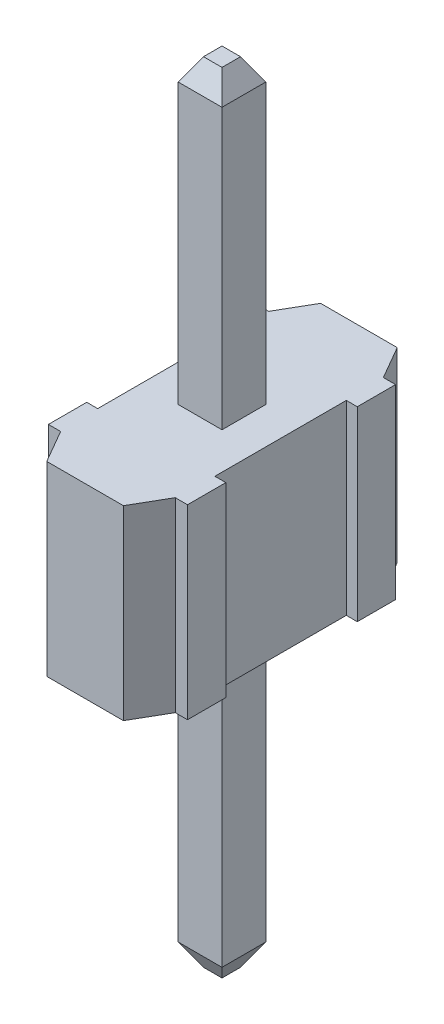
SolidWorks part; units mm, degrees
ref_plane "前视基准面" through (0, 0, 0) normal (0, 0, 1) x (1, 0, 0)
ref_plane "上视基准面" through (0, 0, 0) normal (0, 1, 0) x (1, 0, 0)
ref_plane "右视基准面" through (0, 0, 0) normal (1, 0, 0) x (0, 0, -1)
sketch "草图1" plane through (0, 0, 0) normal (0, 1, 0) x (1, 0, 0)
  line L0 (-1.2877, 0) -> (3.6912, 0) construction
  line L1 (-0.635, -1.25) -> (0.635, -1.25) construction
  line L2 (-0.635, -1.25) -> (-0.635, 1.25) construction
  line L3 (-0.635, 1.25) -> (0.635, 1.25) construction
  line L4 (0.635, -1.25) -> (0.635, 1.25) construction
  line L5 (-0.635, -1.25) -> (0.635, 1.25) construction
  line L6 (-0.635, 1.25) -> (0.635, -1.25) construction
  line L7 (0, 0) -> (-0.635, 0) construction
  line L8 (0, 0) -> (0, -1.25) construction
  line L9 (-0.635, -0.95) -> (-0.5232, -0.95)
  line L10 (-0.5232, -0.95) -> (-0.35, -1.25)
  line L11 (-0.35, -1.25) -> (0.35, -1.25)
  line L12 (-0.635, -0.95) -> (-0.635, -0.6)
  line L13 (-0.635, -0.6) -> (-0.535, -0.6)
  line L14 (-0.535, -0.6) -> (-0.535, 0.6)
  line L15 (-0.35, 1.25) -> (0.35, 1.25)
  line L17 (-0.635, 0.95) -> (-0.5232, 0.95)
  line L18 (-0.635, 0.95) -> (-0.635, 0.6)
  line L19 (-0.635, 0.6) -> (-0.535, 0.6)
  line L20 (-0.5232, 0.95) -> (-0.35, 1.25)
  line L21 (0.5232, 0.95) -> (0.35, 1.25)
  line L22 (0.5232, -0.95) -> (0.35, -1.25)
  line L23 (0.635, -0.95) -> (0.5232, -0.95)
  line L24 (0.635, -0.95) -> (0.635, -0.6)
  line L25 (0.635, -0.6) -> (0.535, -0.6)
  line L26 (0.535, -0.6) -> (0.535, 0.6)
  line L27 (0.635, 0.6) -> (0.535, 0.6)
  line L28 (0.635, 0.95) -> (0.635, 0.6)
  line L29 (0.635, 0.95) -> (0.5232, 0.95)
  point P0 (0, 0)
  point P23 (-0.535, 0)
  point P24 (0, 1.25)
  dimension "D1" = 120
  dimension "D2" = 0.1
  dimension "D3" = 0.6
  dimension "D4" = 0.35
  dimension "D5" = 0.95
extrude "凸台-拉伸1" add sketch "草图1" along normal mid plane 1.7
sketch "草图4" plane through (0, 0, 0) normal (0, 1, 0) x (1, 0, 0)
  line L1 (0.2, -0.2) -> (-0.2, -0.2)
  line L2 (0.2, -0.2) -> (0.2, 0.2)
  line L3 (0.2, 0.2) -> (-0.2, 0.2)
  line L4 (-0.2, -0.2) -> (-0.2, 0.2)
  line L5 (0.2, -0.2) -> (-0.2, 0.2) construction
  line L6 (0.2, 0.2) -> (-0.2, -0.2) construction
  point P0 (0, 0)
  dimension "D1" = 45
  dimension "D2" = 0.4
extrude "凸台-拉伸2" add sketch "草图4" along normal mid plane 7.2
chamfer "倒角1" distance 0.2 angle 30 4 edges at (0, 3.6, -0.2) (0.2, 3.6, 0) (0, 3.6, 0.2) (-0.2, 3.6, 0)
chamfer "倒角2" distance 0.2 angle 30 4 edges at (0, -3.6, 0.2) (0.2, -3.6, 0) (0, -3.6, -0.2) (-0.2, -3.6, 0)
